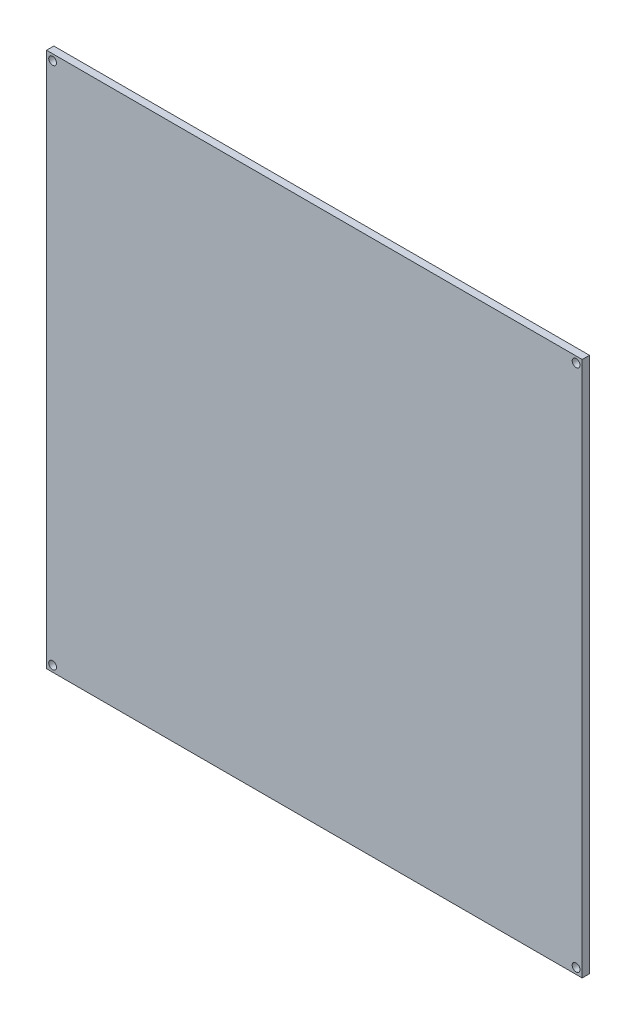
SolidWorks part; units mm, degrees
ref_plane "Plan de face" through (0, 0, 0) normal (0, 0, 1) x (1, 0, 0)
ref_plane "Plan de dessus" through (0, 0, 0) normal (0, 1, 0) x (1, 0, 0)
ref_plane "Plan de droite" through (0, 0, 0) normal (1, 0, 0) x (0, 0, -1)
sketch "Esquisse1" plane through (0, 0, 0) normal (0, 0, 1) x (1, 0, 0)
  line L1 (-110, -110) -> (110, -110)
  line L2 (-110, -110) -> (-110, 110)
  line L3 (-110, 110) -> (110, 110)
  line L4 (110, -110) -> (110, 110)
  line L5 (-110, -110) -> (110, 110) construction
  line L6 (-110, 110) -> (110, -110) construction
  circle A0 centre (-107.5, 107.5) radius 1.6
  circle A1 centre (107.5, 107.5) radius 1.6
  circle A2 centre (107.5, -107.5) radius 1.6
  circle A3 centre (-107.5, -107.5) radius 1.6
  point P0 (0, 0)
  point P17 (0, 0)
  dimension "D3" = 3.2
  dimension "D4" = 2.5
  dimension "D1" = 220
  dimension "D2" = 220
  dimension "D5" = 4
extrude "Boss.-Extru.1" add sketch "Esquisse1" along normal blind 3
